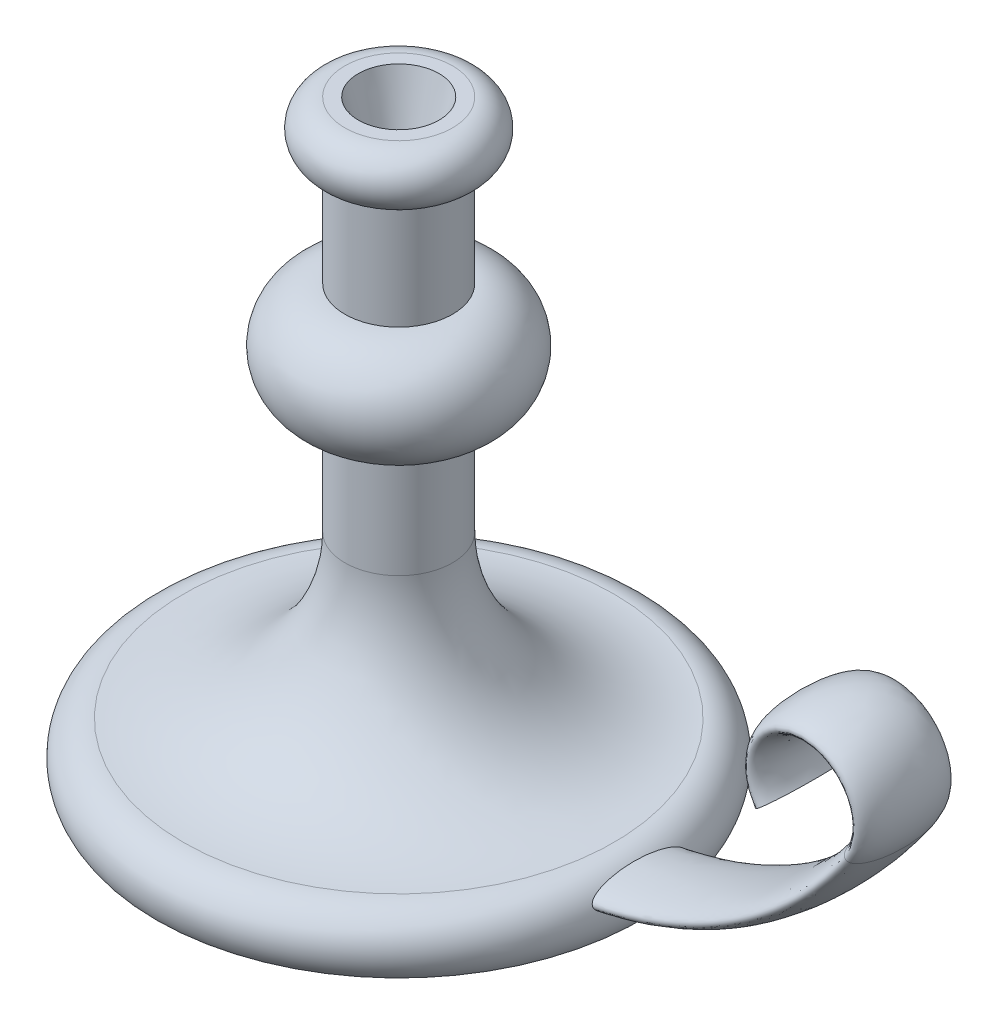
SolidWorks part; units mm, degrees
ref_plane "Front Plane" through (0, 0, 0) normal (0, 0, 1) x (1, 0, 0)
ref_plane "Top Plane" through (0, 0, 0) normal (0, 1, 0) x (1, 0, 0)
ref_plane "Right Plane" through (0, 0, 0) normal (1, 0, 0) x (0, 0, -1)
sketch "Sketch1" plane through (0, 0, 0) normal (0, 0, 1) x (1, 0, 0)
  line L0 (0, 0) -> (0, 220)
  line L1 (0, 0) -> (90, 0)
  line L2 (0, 220) -> (20, 220)
  line L3 (20, 200) -> (20, 160)
  line L4 (20, 120) -> (20, 80)
  arc A0 (20, 220) -> (20, 200) centre (20, 210) cw
  arc A1 (20, 160) -> (20, 120) centre (20, 140) cw
  arc A2 (20, 80) -> (80, 20) centre (80, 80) ccw
  arc A3 (80, 20) -> (90, 0) centre (80, 7.5) cw
  dimension "D4" = 10
  dimension "D6" = 20
  dimension "D8" = 60
  dimension "D9" = 12.5
  dimension "D1" = 20
  dimension "D2" = 220
  dimension "D3" = 90
  dimension "D5" = 80
  dimension "D7" = 40
revolve "Revolve1" add sketch "Sketch1" angle 360 about L0
sketch "Sketch2" plane through (0, 0, 0) normal (0, 0, 1) x (1, 0, 0)
  line L0 (0, 10) -> (60, 10)
  line L1 (0, 227.4356) -> (0, 175.1288) construction
  line L2 (-90, 0) -> (90, 0) construction
  arc A0 (60, 10) -> (183.5921, 75) centre (60, 160) ccw
  arc A1 (183.5921, 75) -> (150.6342, 75) centre (167.1131, 86.3333) ccw
  dimension "D3" = 150
  dimension "D4" = 20
  dimension "D1" = 60
  dimension "D2" = 65
  dimension "D5" = 10
sketch "Sketch3" plane through (0, 0, 0) normal (1, 0, 0) x (0, 0, -1)
  ellipse E0 centre (0, 10) end of major axis (17.5, 10) minor radius 5
  dimension "D1" = 10
  dimension "D2" = 35
sweep "Sweep1" add profiles "Sketch3" path "Sketch2"
sketch "Sketch5" plane through (0, 220, 0) normal (0, 1, 0) x (1, 0, 0)
  circle A0 centre (0, 0) radius 15
  dimension "D1" = 30
extrude "Cut-Extrude1" cut sketch "Sketch5" against normal blind 25 draft 15
